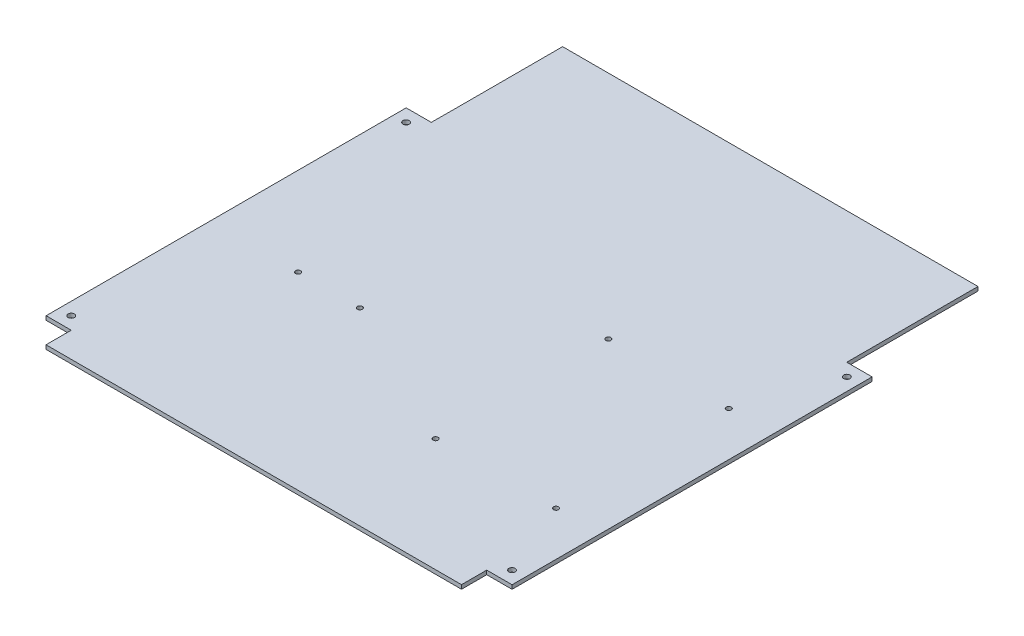
SolidWorks part; units mm, degrees
ref_plane "Front Plane" through (0, 0, 0) normal (0, 0, 1) x (1, 0, 0)
ref_plane "Top Plane" through (0, 0, 0) normal (0, 1, 0) x (1, 0, 0)
ref_plane "Right Plane" through (0, 0, 0) normal (1, 0, 0) x (0, 0, -1)
sketch "Sketch1" plane through (0, 0, 0) normal (0, 1, 0) x (1, 0, 0)
  line L0 (-165.0644, -204.6556) -> (-165.0644, -184.6556)
  line L1 (-165.0644, -184.6556) -> (-204.9744, -184.6556)
  line L2 (-204.9744, -184.6556) -> (-204.9744, 100.9294)
  line L3 (-165.0644, 100.9294) -> (-204.9744, 100.9294)
  line L4 (-165.0644, 100.9294) -> (-164.9644, 121.0194)
  line L5 (-164.9644, 121.0194) -> (-204.9744, 121.0194)
  line L6 (-204.9744, 121.0194) -> (-204.9744, 205.0194)
  line L7 (-204.9744, 205.0194) -> (204.6106, 205.0194)
  line L8 (204.6106, 205.0194) -> (204.6106, 121.0194)
  line L9 (204.6106, 121.0194) -> (164.5106, 120.9294)
  line L10 (164.5106, 120.9294) -> (164.5106, 100.9294)
  line L11 (164.5106, 100.9294) -> (204.6106, 100.9294)
  line L12 (204.6106, 100.9294) -> (202.8606, -184.6556)
  line L13 (202.8606, -184.6556) -> (164.5106, -184.6556)
  line L14 (164.5106, -184.6556) -> (164.5106, -204.6556)
  line L15 (164.5106, -204.6556) -> (-165.0644, -204.6556)
extrude "Boss-Extrude1" add sketch "Sketch1" along normal blind 3.175
sketch "Sketch4" plane through (0, 3.175, 0) normal (0, 1, 0) x (1, 0, 0)
  circle A0 centre (-114.9894, -54.8056) radius 2
  circle A1 centre (-65.9894, -54.8056) radius 2
  circle A2 centre (54.0106, -114.6556) radius 2
  circle A3 centre (149.5106, -114.6556) radius 2
  circle A4 centre (54.0106, 22.3444) radius 2
  circle A5 centre (149.5106, 22.3444) radius 2
extrude "Cut-Extrude2" cut sketch "Sketch4" against normal blind 3.175
sketch "Sketch7" plane through (0, 3.175, 0) normal (0, 1, 0) x (1, 0, 0)
  line L0 (-204.9744, 205.0194) -> (-184.9744, 205.0194)
  line L1 (204.6106, 205.0194) -> (-204.9744, 205.0194) construction
  line L2 (-204.9744, 205.0194) -> (-204.9744, -184.6556)
  line L3 (-204.9744, -184.6556) -> (-184.9744, -184.6556)
  line L4 (-204.9744, -184.6556) -> (-165.0644, -184.6556) construction
  line L5 (-184.9744, -184.6556) -> (-184.9744, 205.0194)
  line L6 (204.6106, 205.0194) -> (184.6106, 205.0194)
  line L7 (204.6106, 205.0194) -> (202.8606, -184.6556)
  line L8 (184.6106, 205.0194) -> (184.6106, -184.6556)
  line L9 (164.5106, -184.6556) -> (202.8606, -184.6556) construction
  line L10 (184.6106, -184.6556) -> (202.8606, -184.6556)
extrude "Cut-Extrude6" cut sketch "Sketch7" against normal blind 3.175
sketch "Sketch8" plane through (0, 3.175, 0) normal (0, 1, 0) x (1, 0, 0)
  line L1 (-164.9644, 121.0194) -> (-184.9744, 121.0194)
  line L2 (-164.9644, 121.0194) -> (-164.9644, 205.0194)
  line L3 (-164.9644, 205.0194) -> (-184.9744, 205.0194)
  line L4 (-184.9744, 121.0194) -> (-184.9744, 205.0194)
  line L5 (164.5106, 120.9294) -> (184.6106, 120.9294)
  line L6 (164.5106, 120.9294) -> (164.5106, 205.0194)
  line L7 (164.5106, 205.0194) -> (184.6106, 205.0194)
  line L8 (184.6106, 120.9294) -> (184.6106, 205.0194)
extrude "Cut-Extrude7" cut sketch "Sketch8" against normal up to surface (3.175 mm away) up to face at (-0.2231, 0, -9.3603)
sketch "Sketch9" plane through (0, 3.175, 0) normal (0, 1, 0) x (1, 0, 0)
  line L0 (-165.0644, 100.9294) -> (-184.9744, 100.9294) construction
  line L1 (184.6106, 100.9294) -> (164.5106, 100.9294) construction
  line L2 (164.5106, -184.6556) -> (184.6106, -184.6556) construction
  line L3 (-184.9744, -184.6556) -> (-165.0644, -184.6556) construction
  circle A0 centre (-175.0194, -174.6556) radius 2.5
  circle A1 centre (174.5606, -174.6556) radius 2.5
  circle A2 centre (174.5606, 90.9344) radius 2.5
  circle A3 centre (-175.0194, 90.9344) radius 2.5
  point P0 (-175.0194, 100.9294)
  point P1 (174.5606, 100.9294)
  point P4 (174.5606, -184.6556)
  point P7 (-175.0194, -184.6556)
  point P10 (-175.0194, -174.6556)
  point P13 (174.5606, -174.6556)
  point P14 (174.5606, 90.9294)
  dimension "D2" = 5
  dimension "D3" = 10
  dimension "D4" = 2
  dimension "D1" = 10
  dimension "D5" = 2
extrude "Cut-Extrude8" cut sketch "Sketch9" against normal up to surface (3.175 mm away) up to face at (-12.9082, 0, 16.3968)
